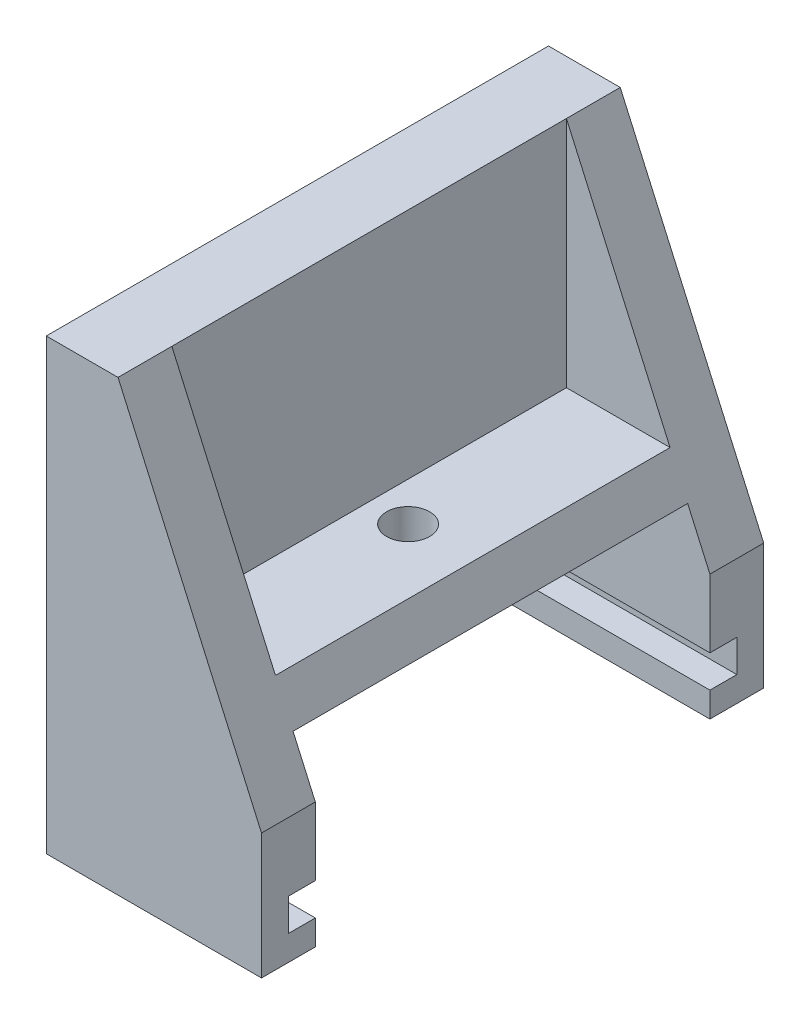
SolidWorks part; units mm, degrees
ref_plane "Front Plane" through (0, 0, 0) normal (0, 0, 1) x (1, 0, 0)
ref_plane "Top Plane" through (0, 0, 0) normal (0, 1, 0) x (1, 0, 0)
ref_plane "Right Plane" through (0, 0, 0) normal (1, 0, 0) x (0, 0, -1)
sketch "Sketch1" plane through (0, 0, 0) normal (0, 0, 1) x (1, 0, 0)
  line L0 (0, 0) -> (0, -25)
  line L1 (0, -25) -> (12, -25)
  line L2 (12, -25) -> (12, -18)
  line L3 (12, -18) -> (4, 0)
  line L4 (4, 0) -> (0, 0)
  dimension "D1" = 25
  dimension "D2" = 12
  dimension "D3" = 7
  dimension "D4" = 4
extrude "Boss-Extrude1" add sketch "Sketch1" against normal blind 28
sketch "Sketch4" plane through (0, 0, 0) normal (-1, 0, 0) x (0, 0, 1)
  line L0 (-28, 0) -> (-28, -25) construction
  line L1 (-25, -15.208) -> (-3, -15.208)
  line L2 (-25, -15.208) -> (-25, -25.208)
  line L3 (-25, -25.208) -> (-3, -25.208)
  line L4 (-3, -15.208) -> (-3, -25.208)
  point P4 (-25, -20.208)
  dimension "D1" = 22
  dimension "D2" = 10
  dimension "D3" = 3
extrude "Cut-Extrude2" cut sketch "Sketch4" against normal blind 15 contours L2 L1 L4 L3
sketch "Sketch5" plane through (0, 0, 0) normal (-1, 0, 0) x (0, 0, 1)
  line L0 (-3, -15.208) -> (-3, -25) construction
  line L1 (-3, -21.8) -> (-1.5, -21.8)
  line L2 (-3, -21.8) -> (-3, -23.6)
  line L3 (-3, -23.6) -> (-1.5, -23.6)
  line L4 (-1.5, -21.8) -> (-1.5, -23.6)
  line L5 (-3, -25) -> (0, -25) construction
  dimension "D1" = 1.8
  dimension "D2" = 1.5
  dimension "D3" = 1.4
extrude "Cut-Extrude3" cut sketch "Sketch5" against normal blind 15
ref_plane "Plane1" through (0, 0, -14) normal (0, 0, 1) x (1, 0, 0)
mirror "Mirror1" about plane through (0, 0, -14) normal (0, 0, 1) of "Cut-Extrude3"
sketch "Sketch6" plane through (0, 0, -14) normal (0, 0, 1) x (1, 0, 0)
  line L0 (4, 0) -> (4, -13)
  line L1 (4, -13) -> (9.7778, -13)
  line L2 (12, -18) -> (4, 0) construction
  line L3 (9.7778, -13) -> (4, 0)
  dimension "D1" = 13
extrude "Cut-Extrude4" cut sketch "Sketch6" against normal mid plane 22
sketch "Sketch7" plane through (0, -13, 0) normal (0, 1, 0) x (1, 0, 0)
  line L0 (-6.6, 14) -> (6.6, 14) construction
  circle A0 centre (6.1728, 14) radius 1.2
  dimension "D1" = 2.4
extrude "Cut-Extrude5" cut sketch "Sketch7" against normal blind 4 contours A0
